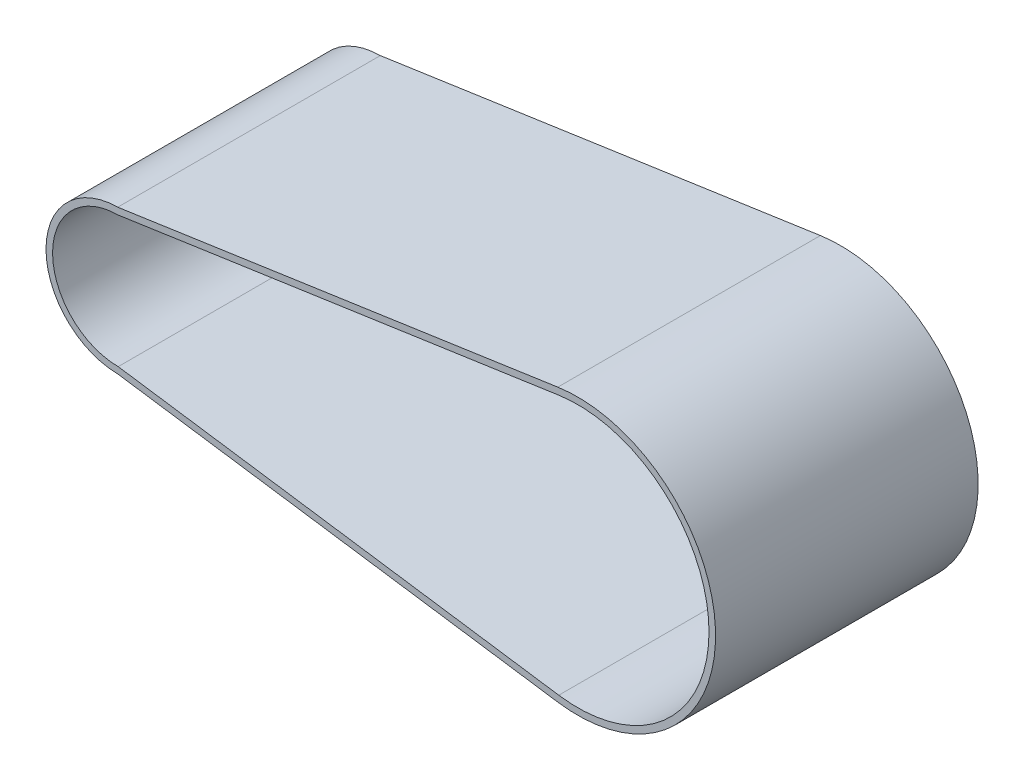
SolidWorks part; units mm, degrees
ref_plane "前视基准面" through (0, 0, 0) normal (0, 0, 1) x (1, 0, 0)
ref_plane "上视基准面" through (0, 0, 0) normal (0, 1, 0) x (1, 0, 0)
ref_plane "右视基准面" through (0, 0, 0) normal (1, 0, 0) x (0, 0, -1)
sketch "草图1" plane through (0, 0, 0) normal (0, 0, 1) x (1, 0, 0)
  line L4 (335.5647, 98.9526) -> (0, 50)
  line L5 (0, -50) -> (335.5647, -98.9526)
  line L6 (0, 0) -> (494.2729, 0) construction
  line L7 (334.8429, 103.9003) -> (-0.3714, 54.9987)
  line L8 (-0.3714, -54.9987) -> (334.8429, -103.9003)
  arc A4 (0, 50) -> (0, -50) centre (0, 0) ccw
  arc A5 (335.5647, -98.9526) -> (335.5647, 98.9526) centre (350, 0) ccw
  arc A6 (-0.3714, 54.9987) -> (-0.3714, -54.9987) centre (0, 0) ccw
  arc A7 (334.8429, -103.9003) -> (334.8429, 103.9003) centre (350, 0) ccw
  dimension "D2" = 200
  dimension "D1" = 100
  dimension "D3" = 350
  dimension "D4" = 5
extrude "凸台-拉伸2" add sketch "草图1" along normal blind 200
